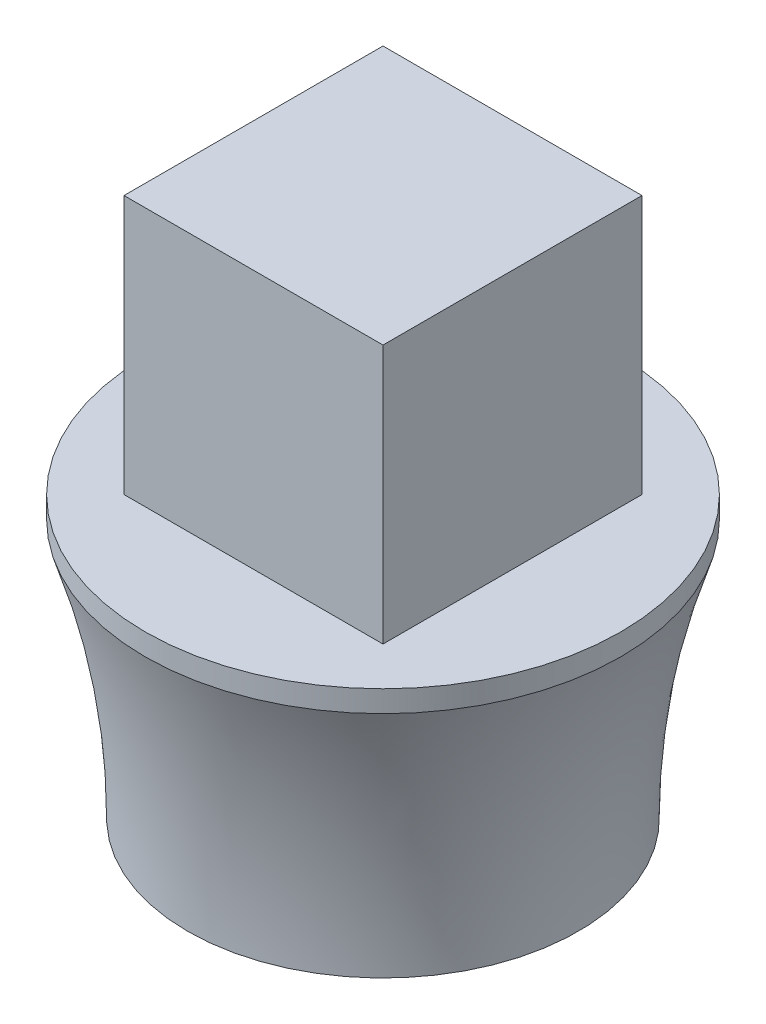
SolidWorks part; units mm, degrees
ref_plane "Front Plane" through (0, 0, 0) normal (0, 0, 1) x (1, 0, 0)
ref_plane "Top Plane" through (0, 0, 0) normal (0, 1, 0) x (1, 0, 0)
ref_plane "Right Plane" through (0, 0, 0) normal (1, 0, 0) x (0, 0, -1)
sketch "Sketch1" plane through (0, 0, 0) normal (0, 0, 1) x (1, 0, 0)
  line L0 (0, 0) -> (0, 76.2) construction
  line L1 (0, 76.2) -> (70, 76.2) construction
  line L2 (0, 0) -> (55, 0) construction
  line L3 (55, 0) -> (55, 76.2)
  line L4 (55, 76.2) -> (70, 76.2)
  line L5 (55, 0) -> (57.5, 0) construction
  line L6 (57.5, 0) -> (57.5, 76.2) construction
  line L7 (55, 0) -> (57.5, 0)
  arc A1 (57.5, 0) -> (70, 76.2) centre (296.0076, 0) cw
  dimension "D1" = 55
  dimension "D2" = 70
  dimension "D3" = 76.2
  dimension "D4" = 2.5
revolve "Revolve1" add sketch "Sketch1" angle 360 about L0
sketch "Sketch2" plane through (0, 76.2, 0) normal (0, 1, 0) x (1, 0, 0)
  circle A0 centre (0, 0) radius 70
  circle A2 centre (0, 0) radius 70 construction
  circle M2 centre (0, 0) radius 55
  circle M4 centre (0, 0) radius 70
extrude "Boss-Extrude1" add sketch "Sketch2" along normal blind 6.35 contours M4 M2 | M2
sketch "Sketch5" plane through (0, 82.55, 0) normal (0, 1, 0) x (1, 0, 0)
  line L1 (-38.1, 38.1) -> (38.1, 38.1)
  line L2 (-38.1, 38.1) -> (-38.1, -38.1)
  line L3 (-38.1, -38.1) -> (38.1, -38.1)
  line L4 (38.1, 38.1) -> (38.1, -38.1)
  line L5 (-38.1, 38.1) -> (38.1, -38.1) construction
  line L6 (-38.1, -38.1) -> (38.1, 38.1) construction
  point P0 (0, 0)
  dimension "D1" = 76.2
  dimension "D2" = 76.2
extrude "Boss-Extrude3" add sketch "Sketch5" along normal blind 76.2
sketch "Sketch6" plane through (0, 0, 38.1) normal (0, 0, 1) x (1, 0, 0)
  line L0 (29.0241, 275.1083) -> (278.3574, 275.1083) construction
